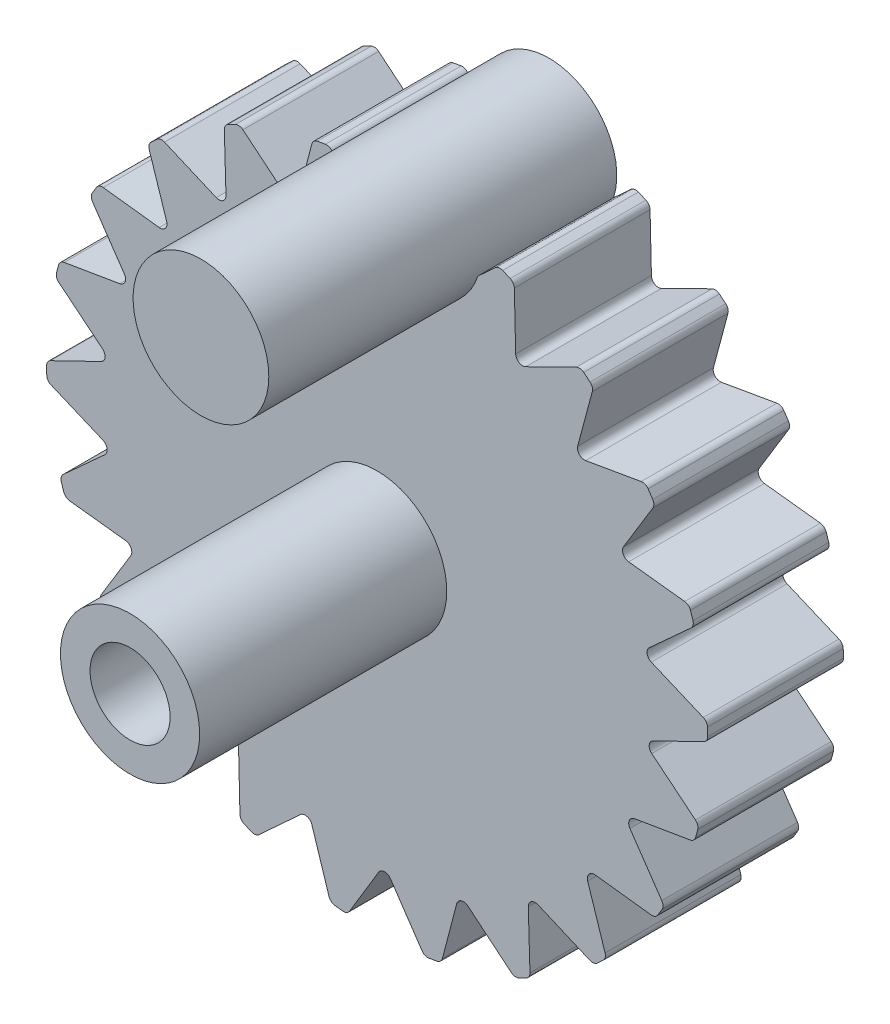
SolidWorks part; units mm, degrees
ref_plane "Plan de face" through (0, 0, 0) normal (0, 0, 1) x (1, 0, 0)
ref_plane "Plan de dessus" through (0, 0, 0) normal (0, 1, 0) x (1, 0, 0)
ref_plane "Plan de droite" through (0, 0, 0) normal (1, 0, 0) x (0, 0, -1)
sketch "Esquisse1" plane through (0, 0, 0) normal (0, 0, 1) x (1, 0, 0)
  circle A0 centre (0, 0) radius 4.75
  dimension "D1" = 9.5
extrude "Boss.-Extru.1" add sketch "Esquisse1" along normal blind 1.95
sketch "Esquisse2" plane through (0, 0, 1.95) normal (0, 0, 1) x (1, 0, 0)
  line L0 (0, 0) -> (3.5055, 3.2053) construction
  line L1 (3.1175, 3.6296) -> (3.8935, 2.7809)
  line L2 (3.1175, 3.6296) -> (2.8413, 2.598)
  line L3 (2.8413, 2.598) -> (3.8935, 2.7809)
  circle A0 centre (0, 0) radius 4.75 construction
  point P7 (3.5055, 3.2053)
  dimension "D1" = 1.15
  dimension "D2" = 0.9
extrude "Enlèv. mat.-Extru.1" cut sketch "Esquisse2" against normal blind 1.95
fillet "Congé1" radius 0.1 3 edges at (2.8413, 2.598, 0.975) (3.8556, 2.7743, 0.975) (3.1076, 3.5924, 0.975)
pattern_circular "Répétition circulaire1" count 22 over 360 about axis through (0, 0, 0) along (0, 0, 1) of "Congé1", "Enlèv. mat.-Extru.1"
sketch "Esquisse3" plane through (0, 0, 1.95) normal (0, 0, 1) x (1, 0, 0)
  circle A0 centre (0, 0) radius 1
  dimension "D1" = 2
extrude "Boss.-Extru.2" add sketch "Esquisse3" along normal blind 6.75 from vertex at -1.95 starting at point (3.0912, 3.5315, 0)
sketch "Esquisse4" plane through (0, 0, 1.95) normal (0, 0, 1) x (1, 0, 0)
  line L0 (0, 0) -> (0.5503, 4.718) construction
  circle A0 centre (0, 0) radius 4.75 construction
  circle A1 centre (0.5184, 4.4449) radius 0.975
  dimension "D1" = 1.95
  dimension "D2" = 4.475
extrude "Boss.-Extru.3" add sketch "Esquisse4" along normal blind 5 from vertex at -1.95 starting at point (-0.6446, 4.6488, 0)
sketch "Esquisse5" plane through (0, 0, 6.75) normal (0, 0, 1) x (1, 0, 0)
  line L0 (0, 0) -> (0.5184, 4.4449) construction
  line L1 (-1.2803, 1.1561) -> (1.512, 0.8304)
  line L2 (-1.512, -0.8304) -> (1.2803, -1.1561)
  line L3 (0.1159, 0.9933) -> (-0.1159, -0.9933) construction
  arc A0 (-1.2803, 1.1561) -> (-1.512, -0.8304) centre (0, 0) ccw
  arc A1 (1.2803, -1.1561) -> (1.512, 0.8304) centre (0, 0) ccw
  point P11 (0, 0)
  dimension "D1" = 3.45
  dimension "D2" = 2
  dimension "D3" = 2
extrude "Enlèv. mat.-Extru.2" cut sketch "Esquisse5" against normal blind 1.25
sketch "Esquisse6" plane through (0, 0, 0) normal (0, 0, -1) x (-1, 0, 0)
  circle A0 centre (0, 0) radius 0.575
  dimension "D1" = 1.15
extrude "Enlèv. mat.-Extru.3" cut sketch "Esquisse6" against normal blind 8.25
scale "Scale1" scale about centroid uniform scaling yes scale factor 6.5
